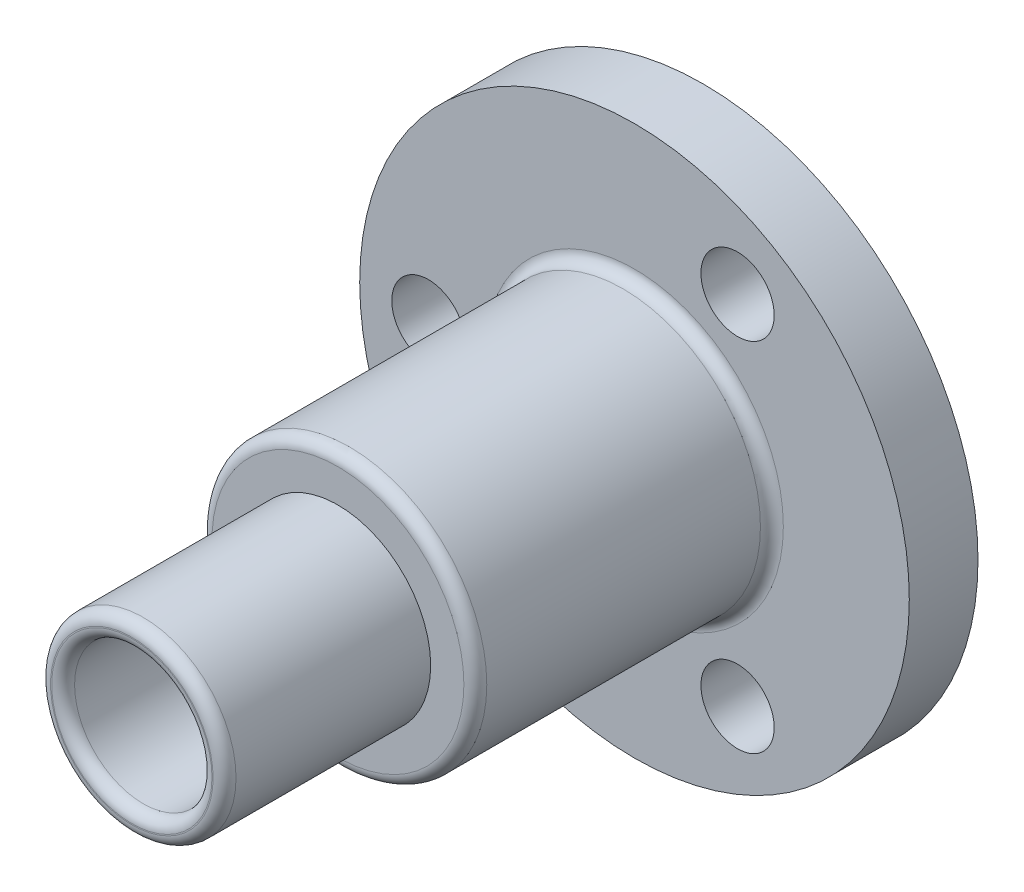
SolidWorks part; units mm, degrees
ref_plane "Alzado" through (0, 0, 0) normal (1, 0, 0) x (0, 1, 0)
ref_plane "Planta" through (0, 0, 0) normal (0, 0, 1) x (0, 1, 0)
ref_plane "Vista lateral" through (0, 0, 0) normal (0, 1, 0) x (-1, 0, 0)
sketch "Croquis1" plane through (0, 0, 0) normal (0, 0, 1) x (0, 1, 0)
  circle A0 centre (0, 0) radius 12
  circle A1 centre (0, 0) radius 9 construction
  circle A2 centre (0, 9) radius 1.6
  circle A3 centre (7.7942, -4.5) radius 1.6
  circle A4 centre (-7.7942, -4.5) radius 1.6
  circle A5 centre (0, 0) radius 3.5
  point P13 (0, 0)
  dimension "D1" = 24
  dimension "D2" = 18
  dimension "D3" = 3.2
  dimension "D5" = 7
  dimension "D4" = 3
extrude "Saliente-Extruir1" add sketch "Croquis1" along normal blind 3
sketch "Croquis2" plane through (0, 0, 3) normal (0, 0, 1) x (1, 0, 0)
  circle A0 centre (0, 0) radius 3
  circle A1 centre (0, 0) radius 6
  dimension "D1" = 6
  dimension "D2" = 12
extrude "Saliente-Extruir2" add sketch "Croquis2" along normal blind 12.95
sketch "Croquis3" plane through (0, 0, 15.95) normal (0, 0, 1) x (1, 0, 0)
  circle A0 centre (0, 0) radius 3
  circle A1 centre (0, 0) radius 4.05
  dimension "D1" = 8.1
  dimension "D2" = 6
extrude "Saliente-Extruir3" add sketch "Croquis3" along normal blind 9
fillet "Redondeo1" radius 0.5 4 edges at (3, 0, 24.95) (4.05, 0, 24.95) (6, 0, 15.95) (6, 0, 3)
